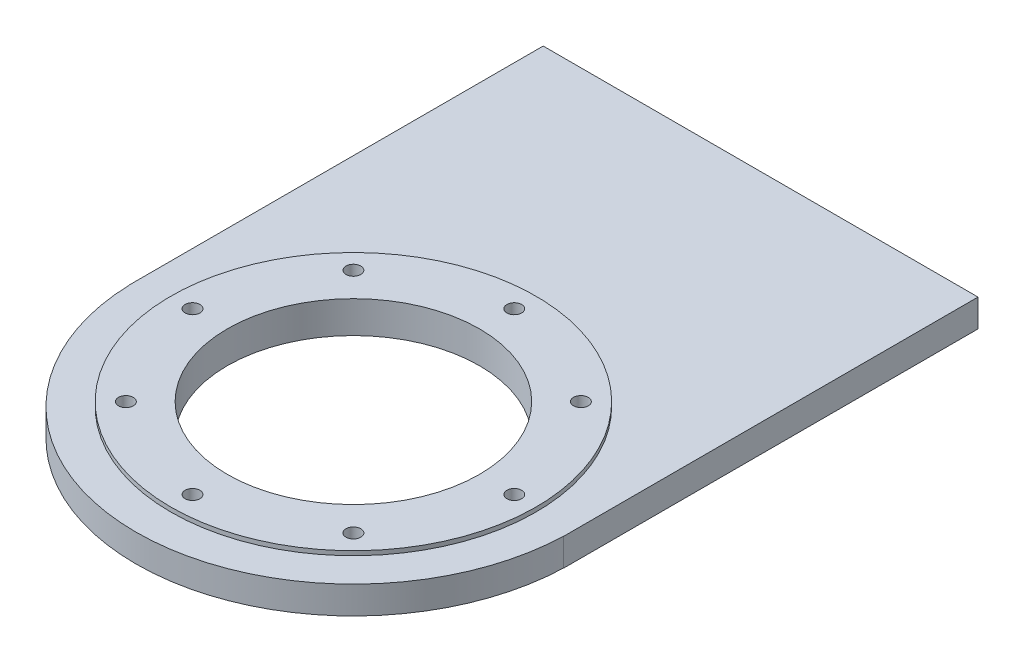
SolidWorks part; units mm, degrees
material "Aleación 6061"
ref_plane "Alzado" through (0, 0, 0) normal (0, 0, 1) x (1, 0, 0)
ref_plane "Planta" through (0, 0, 0) normal (0, 1, 0) x (1, 0, 0)
ref_plane "Vista lateral" through (0, 0, 0) normal (1, 0, 0) x (0, 0, -1)
sketch "Sk_Pared" plane through (0, 0, 0) normal (0, 1, 0) x (1, 0, 0)
  line L1 (-50, -171.65) -> (50, -171.65)
  line L2 (-50, -171.65) -> (-50, -76.35)
  line L3 (-50, -76.35) -> (50, -76.35)
  line L4 (50, -171.65) -> (50, -76.35)
  line L5 (-50, -171.65) -> (50, -76.35) construction
  line L6 (-50, -76.35) -> (50, -171.65) construction
  point P0 (0, -124)
  dimension "D1" = 100
  dimension "D2" = 95.3
  dimension "D3" = 124
extrude "Pared" add sketch "Sk_Pared" along normal blind 6.35 from offset 36.1
sketch "Sk_Cabeza" plane through (0, 0, 0) normal (0, 1, 0) x (1, 0, 0)
  circle A0 centre (0, -170) radius 50
  dimension "D1" = 100
  dimension "D2" = 170
extrude "Cabeza" add sketch "Sk_Cabeza" along normal blind 6.35 from offset 36.1
sketch "Sk_Asiento_1mm" plane through (0, 0, 0) normal (0, 1, 0) x (1, 0, 0)
  circle A0 centre (0, -170) radius 42
  circle A1 centre (0, -170) radius 29
  dimension "D1" = 84
  dimension "D3" = 58
  dimension "D2" = 170
  dimension "D4" = 170
extrude "Asiento_1mm" add sketch "Sk_Asiento_1mm" along normal blind 1 from offset 29.75
sketch "Sk_Paso_boss_J2" plane through (0, 0, 0) normal (0, 1, 0) x (1, 0, 0)
  circle A0 centre (0, -170) radius 29
  dimension "D1" = 58
  dimension "D2" = 170
extrude "Paso_boss_J2" cut sketch "Sk_Paso_boss_J2" along normal blind 7.35 from offset 36.1
sketch "Sk_Pasantes_M3_estator_J2" plane through (0, 0, 0) normal (0, 1, 0) x (1, 0, 0)
  circle A0 centre (37, -170) radius 1.7
  circle A1 centre (26.163, -196.163) radius 1.7
  circle A2 centre (0, -207) radius 1.7
  circle A3 centre (-26.163, -196.163) radius 1.7
  circle A4 centre (-37, -170) radius 1.7
  circle A5 centre (-26.163, -143.837) radius 1.7
  circle A6 centre (0, -133) radius 1.7
  circle A7 centre (26.163, -143.837) radius 1.7
  dimension "D1" = 3.4
  dimension "D4" = 3.4
  dimension "D7" = 3.4
  dimension "D9" = 3.4
  dimension "D12" = 3.4
  dimension "D15" = 3.4
  dimension "D18" = 3.4
  dimension "D20" = 3.4
  dimension "D2" = 37
  dimension "D3" = 170
  dimension "D5" = 26.163
  dimension "D6" = 196.163
  dimension "D8" = 207
  dimension "D10" = 26.163
  dimension "D11" = 196.163
  dimension "D13" = 37
  dimension "D14" = 170
  dimension "D16" = 26.163
  dimension "D17" = 143.837
  dimension "D19" = 133
  dimension "D21" = 26.163
  dimension "D22" = 143.837
extrude "Pasantes_M3_estator_J2" cut sketch "Sk_Pasantes_M3_estator_J2" along normal blind 7.35 from offset 36.1
sketch "Sk_Pasantes_M4_angulos" plane through (0, 0, 0) normal (0, 1, 0) x (1, 0, 0)
  circle A0 centre (-21, -89.11) radius 2.25
  circle A1 centre (21, -89.11) radius 2.25
  dimension "D1" = 4.5
  dimension "D4" = 4.5
  dimension "D2" = 21
  dimension "D3" = 89.11
  dimension "D5" = 21
  dimension "D6" = 89.11
sketch "Sk_Rosca_M4_desde_abajo" plane through (0, 0, 76.35) normal (0, 0, -1) x (-1, 0, 0)
  circle A0 centre (35, -34.75) radius 1.65
  circle A1 centre (-35, -34.75) radius 1.65
sketch "Sk_Rosca_M3_desde_abajo" plane through (0, 0, 76.35) normal (0, 0, -1) x (-1, 0, 0)
  circle A0 centre (42, -32.9225) radius 1.25
  circle A1 centre (20, -32.9225) radius 1.25
  circle A2 centre (-20, -32.9225) radius 1.25
  circle A3 centre (-42, -32.9225) radius 1.25
extrude "Rosca_M3_desde_abajo" cut sketch "Sk_Rosca_M3_desde_abajo" against normal blind 9
